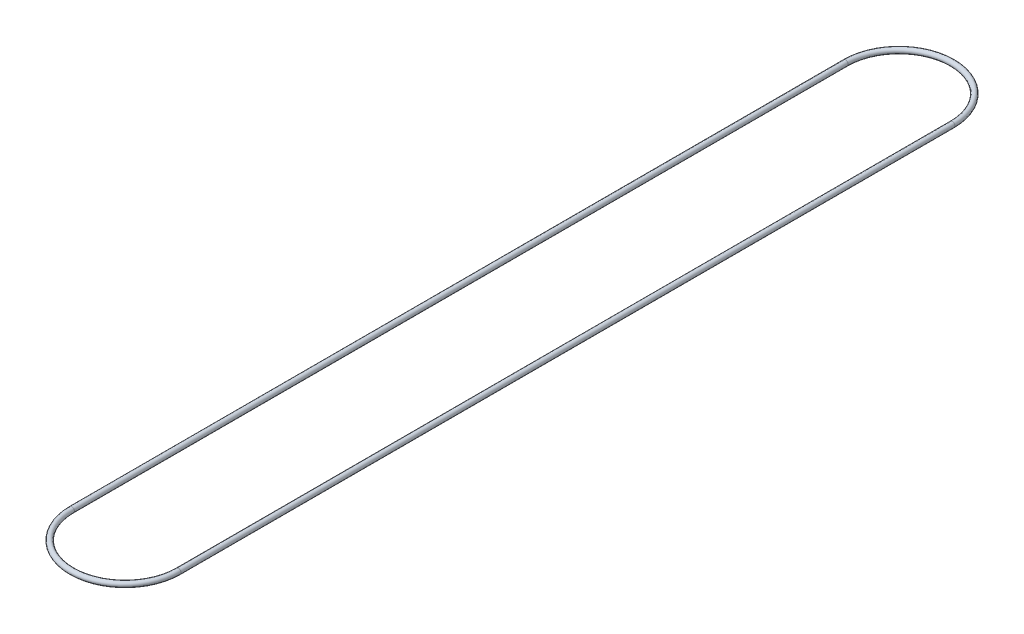
SolidWorks part; units mm, degrees
ref_plane "Plan de face" through (0, 0, 0) normal (0, 0, 1) x (1, 0, 0)
ref_plane "Plan de dessus" through (0, 0, 0) normal (0, 1, 0) x (1, 0, 0)
ref_plane "Plan de droite" through (0, 0, 0) normal (1, 0, 0) x (0, 0, -1)
sketch "Esquisse1" plane through (0, 0, 0) normal (0, 1, 0) x (1, 0, 0)
  line L1 (-5, 0) -> (-5, -72.509)
  line L2 (5, 0) -> (5, -72.509)
  arc A0 (5, 0) -> (-5, 0) centre (0, 0) ccw
  arc A1 (-5, -72.509) -> (5, -72.509) centre (0, -72.509) ccw
  dimension "D1" = 10
  dimension "D2" = 72.509
sketch "Esquisse2" plane through (0, 0, 0) normal (0, 0, 1) x (1, 0, 0)
  line L0 (5, 0) -> (-5, 0) construction
  circle A0 centre (-5, 0) radius 0.25
  dimension "D1" = 0.5
sweep "Balayage1" add profiles "Esquisse2" path "Esquisse1"
